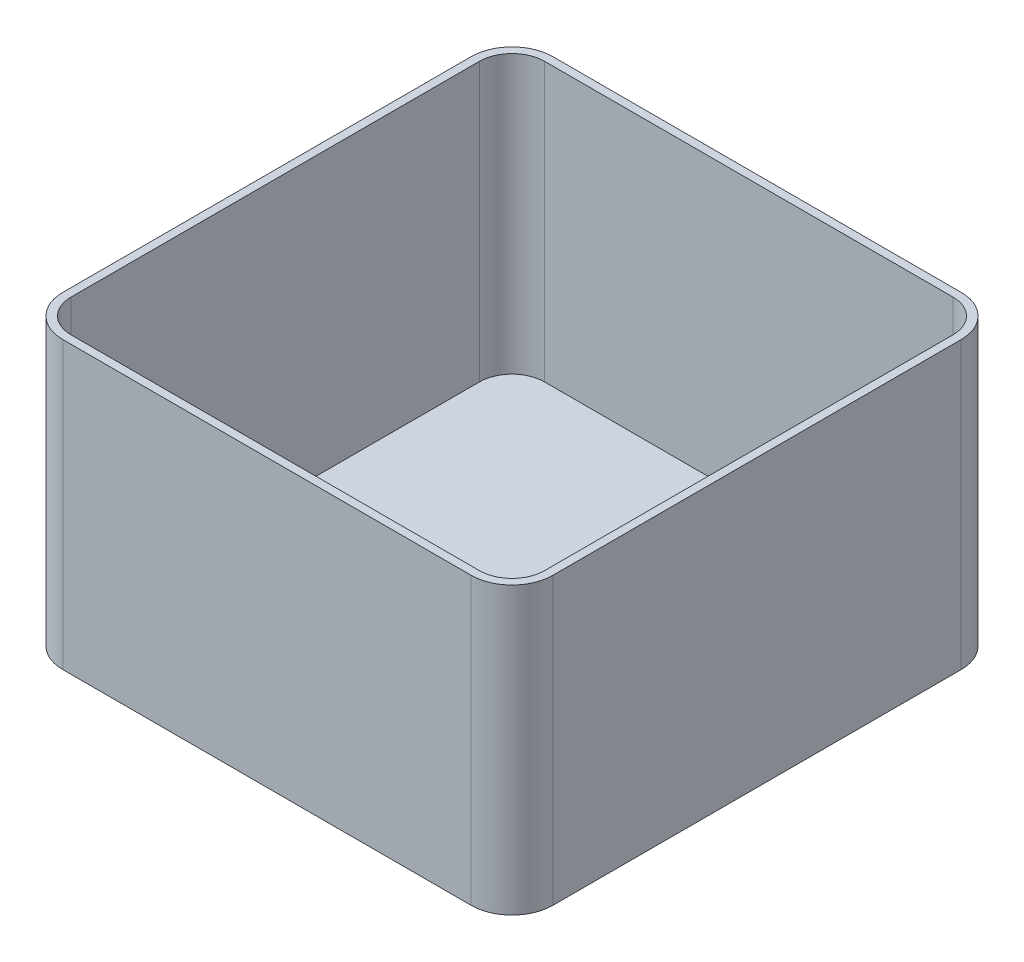
SolidWorks part; units mm, degrees
ref_plane "Front Plane" through (0, 0, 0) normal (0, 0, 1) x (1, 0, 0)
ref_plane "Top Plane" through (0, 0, 0) normal (0, 1, 0) x (1, 0, 0)
ref_plane "Right Plane" through (0, 0, 0) normal (1, 0, 0) x (0, 0, -1)
sketch "Sketch1" plane through (0, 0, 0) normal (0, 1, 0) x (1, 0, 0)
  line L1 (-25, -30) -> (25, -30)
  line L2 (-30, -25) -> (-30, 25)
  line L3 (-25, 30) -> (25, 30)
  line L4 (30, -25) -> (30, 25)
  line L5 (0, 30) -> (0, -30) construction
  line L6 (-30, 0) -> (30, 0) construction
  arc A0 (-25, -30) -> (-30, -25) centre (-25, -25) cw
  arc A1 (25, -30) -> (30, -25) centre (25, -25) ccw
  arc A2 (25, 30) -> (30, 25) centre (25, 25) cw
  arc A3 (-30, 25) -> (-25, 30) centre (-25, 25) cw
  point P0 (0, 0)
  point P6 (-30, -30)
  point P14 (-30, 30)
  dimension "D2" = 5
  dimension "D1" = 60
extrude "Boss-Extrude1" add sketch "Sketch1" along normal blind 35
shell "Shell1" thickness 1
sketch "Sketch3" plane through (0, 1, 0) normal (0, 1, 0) x (1, 0, 0)
  circle A0 centre (0, 0) radius 5 construction
  dimension "D1" = 10
